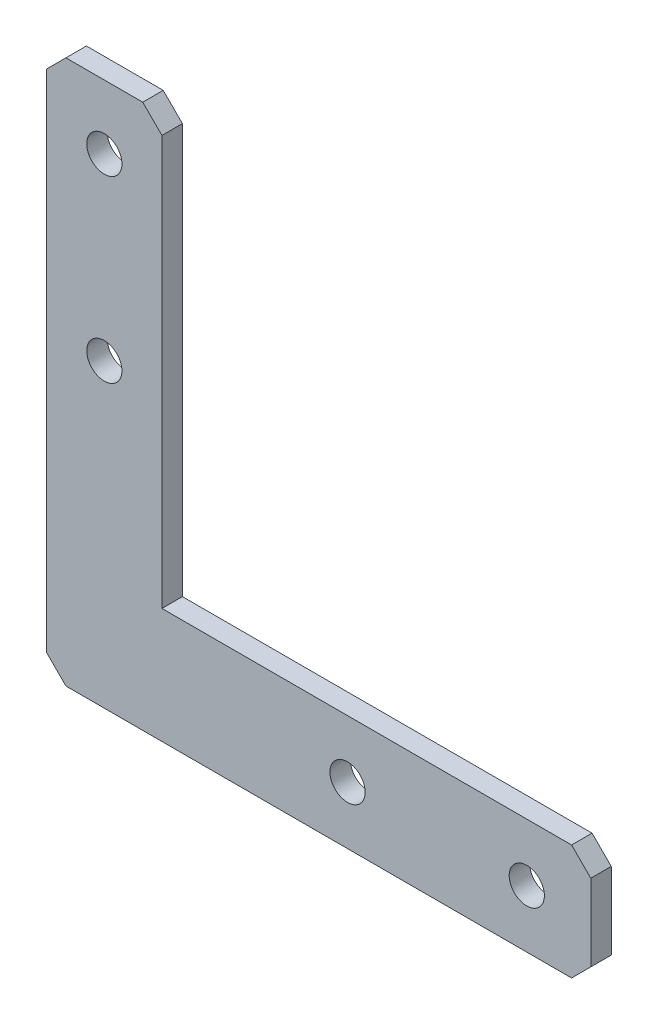
SolidWorks part; units mm, degrees
ref_plane "Front Plane" through (0, 0, 0) normal (0, 0, 1) x (1, 0, 0)
ref_plane "Top Plane" through (0, 0, 0) normal (0, 1, 0) x (1, 0, 0)
ref_plane "Right Plane" through (0, 0, 0) normal (1, 0, 0) x (0, 0, -1)
ref_plane "Plane1" through (0, 0, 0) normal (0, 0, 1) x (1, 0, 0)
sketch "Sketch1" plane through (0, 0, 0) normal (0, 0, 1) x (1, 0, 0)
  line L0 (0, 82) -> (0, 3)
  line L1 (0, 3) -> (3, 0)
  line L2 (3, 0) -> (82, 0)
  line L3 (82, 0) -> (85, 3)
  line L4 (85, 3) -> (85, 15)
  line L5 (85, 15) -> (82, 18)
  line L6 (82, 18) -> (18, 18)
  line L7 (18, 18) -> (18, 82)
  line L8 (18, 82) -> (15, 85)
  line L9 (15, 85) -> (3, 85)
  line L10 (3, 85) -> (0, 82)
  circle A0 centre (75, 9) radius 2.75
  circle A1 centre (47, 9) radius 2.75
  circle A2 centre (9, 47) radius 2.75
  circle A3 centre (9, 75) radius 2.75
extrude "Boss-Extrude1" add sketch "Sketch1" against normal blind 3.2
